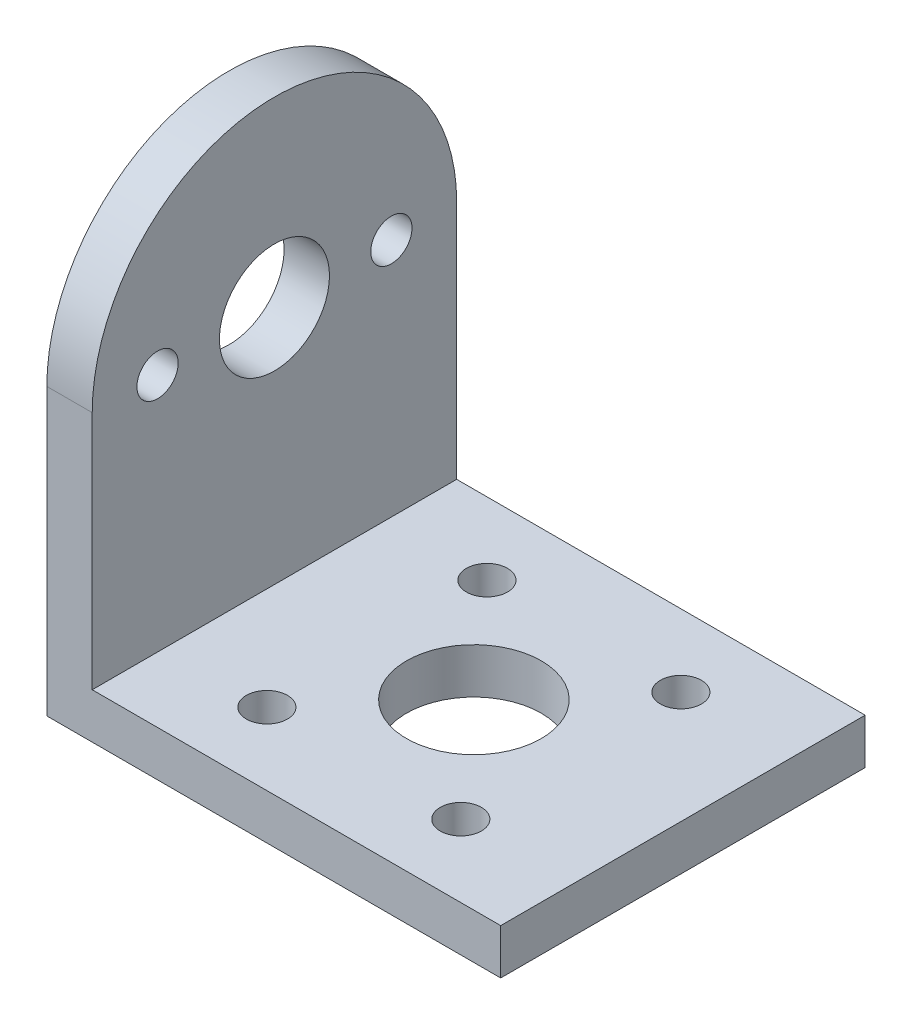
SolidWorks part; units mm, degrees
ref_plane "前视基准面" through (0, 0, 0) normal (0, 0, 1) x (1, 0, 0)
ref_plane "上视基准面" through (0, 0, 0) normal (0, 1, 0) x (1, 0, 0)
ref_plane "右视基准面" through (0, 0, 0) normal (1, 0, 0) x (0, 0, -1)
sketch "草图1" plane through (0, 0, 0) normal (1, 0, 0) x (0, 0, -1)
  line L0 (-13.25, 0) -> (-13.25, -20.75)
  line L1 (-13.25, -20.75) -> (13.25, -20.75)
  line L2 (13.25, -20.75) -> (13.25, 0)
  line L3 (0, 0) -> (8.5, 0) construction
  line L4 (0, 0) -> (0, 23.4695) construction
  arc A0 (13.25, 0) -> (-13.25, 0) centre (0, 0) ccw
  circle A1 centre (0, 0) radius 4
  circle A2 centre (8.5, 0) radius 1.5
  circle A3 centre (-8.5, 0) radius 1.5
  dimension "D1" = 26.5
  dimension "D2" = 8
  dimension "D5" = 3
  dimension "D3" = 20.75
  dimension "D4" = 8.5
extrude "凸台-拉伸1" add sketch "草图1" along normal blind 3.3
sketch "草图2" plane through (0, -20.75, 0) normal (0, -1, 0) x (1, 0, 0)
  line L0 (0, -13.25) -> (33, -13.25)
  line L1 (33, -13.25) -> (33, 13.25)
  line L2 (33, 13.25) -> (0, 13.25)
  line L3 (0, 13.25) -> (0, -13.25)
  line L4 (33, 0) -> (17.8, 0) construction
  line L5 (17.8, 0) -> (17.8, -25.7878) construction
  circle A0 centre (17.8, 0) radius 4.9
  circle A1 centre (24.85, -8) radius 1.4954
  circle A2 centre (24.85, 8) radius 1.4954
  circle A3 centre (10.75, 8) radius 1.4954
  circle A4 centre (10.75, -8) radius 1.4954
  dimension "D3" = 9.8
  dimension "D4" = 8.15
  dimension "D5" = 8
  dimension "D1" = 33
  dimension "D2" = 15.2
extrude "凸台-拉伸2" add sketch "草图2" against normal blind 3.3
